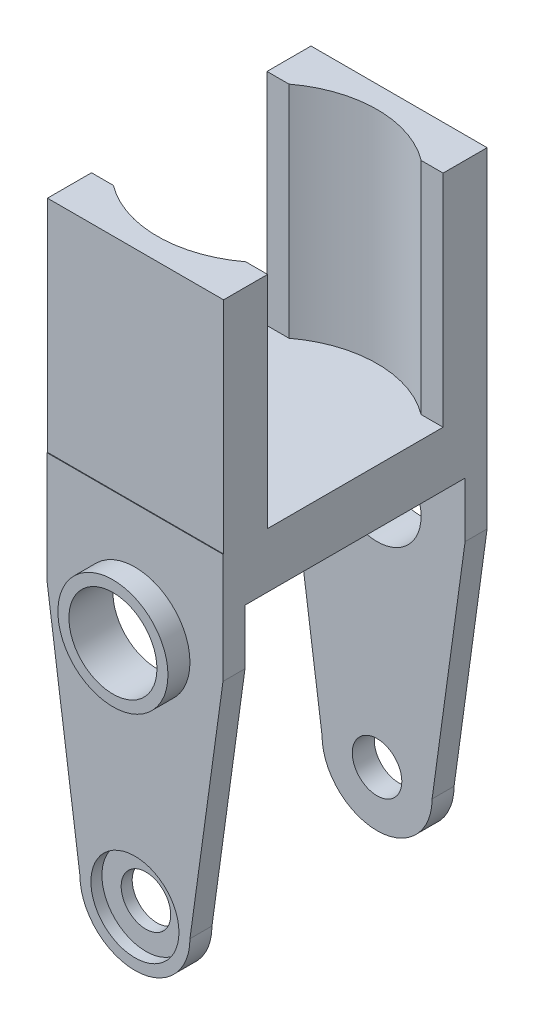
SolidWorks part; units mm, degrees
ref_plane "前视基准面" through (0, 0, 0) normal (0, 0, 1) x (1, 0, 0)
ref_plane "上视基准面" through (0, 0, 0) normal (0, 1, 0) x (1, 0, 0)
ref_plane "右视基准面" through (0, 0, 0) normal (1, 0, 0) x (0, 0, -1)
sketch "草图4" plane through (0, 0, 0) normal (0, 0, 1) x (1, 0, 0)
  line L9 (-8, 0) -> (-5, -21.75)
  line L12 (8, 0) -> (5, -21.75)
  line L16 (-5, 10) -> (5, 10)
  line L24 (-5, 10) -> (-8, 10)
  line L25 (-8, 10) -> (-8, 0)
  line L26 (8, 0) -> (8, 10)
  line L27 (8, 10) -> (5, 10)
  arc A4 (-5, -21.75) -> (5, -21.75) centre (0, -21.75) ccw
  circle A5 centre (0, 0) radius 4
extrude "凸台-拉伸1" add sketch "草图4" along normal blind 24
hole_wizard "M4 六角凹头盖的柱孔1" positions "3D草图1" profile "草图5" counterbore size "M4" standard "BSI" end condition through all
sketch3d "3D草图1"
  line L0 (0, -21.75, 24) -> (0, -21.75, 0) construction
  point P0 (0, -21.75, 24)
sketch "草图5" plane through (0, -21.75, 24) normal (1, 0, 0) x (0, -1, 0)
  line L0 (0, 0) -> (0, 24)
  line L1 (0, 24) -> (2.25, 24)
  line L3 (2.25, 24) -> (2.25, 1)
  line L4 (2.25, 1) -> (4, 1)
  line L5 (4, 1) -> (4, 0)
  line L7 (4, 0) -> (0, 0)
  line L11 (0, -6.35) -> (0, 107.95) construction
  dimension "通孔孔直径" = 4.5
  dimension "通孔孔深度" = 24
  dimension "柱形沉头孔直径" = 8
  dimension "柱形沉头孔深度" = 1
ref_plane "基准面2" through (0, 0, 24) normal (0, 0, 1) x (1, 0, 0)
sketch "草图7" plane through (0, 0, 24) normal (0, 0, 1) x (1, 0, 0)
  circle A0 centre (0, 0) radius 4
  circle A1 centre (0, 0) radius 5
extrude "凸台-拉伸2" add sketch "草图7" along normal blind 2 and the other way blind 26
ref_plane "基准面3" through (0, 10, 0) normal (0, 1, 0) x (1, 0, 0)
sketch "草图8" plane through (0, 10, 0) normal (0, 1, 0) x (1, 0, 0)
  line L0 (-8, 0) -> (8, 0)
  line L1 (-8, 0) -> (-8, -4)
  line L2 (-8, -4) -> (-6.009, -4)
  line L6 (8, -23.9461) -> (8, -19.9461)
  line L11 (8, -4) -> (6.009, -4)
  line L12 (8, 0) -> (8, -4)
  line L13 (8, -19.9461) -> (6.009, -19.9461)
  line L14 (-8, -19.9461) -> (-6.009, -19.9461)
  line L15 (-8, -23.9461) -> (-8, -19.9461)
  line L16 (-8, -23.9461) -> (8, -23.9461)
  arc A5 (-6.009, -4) -> (6.009, -4) centre (0, -11.9731) cw
  arc A6 (-6.009, -19.9461) -> (6.009, -19.9461) centre (0, -11.9731) ccw
extrude "凸台-拉伸3" add sketch "草图8" along normal blind 20
ref_plane "基准面4" through (-8, 0, 0) normal (-1, 0, 0) x (0, 0, 1)
sketch "草图9" plane through (-8, 0, 0) normal (-1, 0, 0) x (0, 0, 1)
  line L0 (0, 0) -> (2, 0)
  line L1 (24, 0) -> (0, 0) construction
  line L2 (2, 0) -> (2, 5)
  line L3 (2, 5) -> (22, 5)
  line L4 (22, 5) -> (22, -27)
  line L5 (22, -27) -> (2, -27)
  line L6 (2, -27) -> (2, 0)
extrude "切除-拉伸1" cut sketch "草图9" against normal blind 20 contours L6 L5 L4 L3 L2
